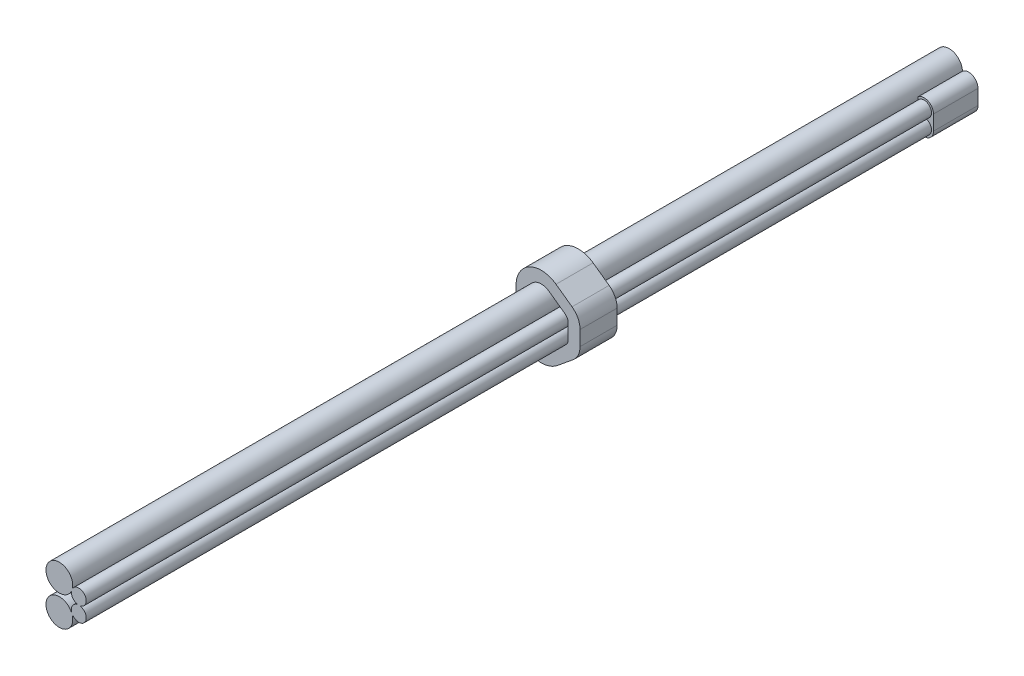
SolidWorks part; units mm, degrees
material "PVC 0.007 Plasticized"
ref_plane "Front Plane" through (0, 0, 0) normal (0, 0, 1) x (1, 0, 0)
ref_plane "Top Plane" through (0, 0, 0) normal (0, 1, 0) x (1, 0, 0)
ref_plane "Right Plane" through (0, 0, 0) normal (1, 0, 0) x (0, 0, -1)
ref_plane "Plane1" through (0, 0, 27.5) normal (0, 0, 1) x (1, 0, 0)
sketch "Sketch1" plane through (0, 0, 27.5) normal (0, 0, 1) x (1, 0, 0)
  line L0 (0.6794, -0.5903) -> (0.6794, -1.4197)
  line L1 (-0.9, -2.01) -> (-0.9, 0)
  line L2 (1.6306, -1.8389) -> (0.5699, -2.7066)
  line L3 (0.8727, -1.7901) -> (0.924, -1.7648)
  line L4 (0.5253, 0.7308) -> (1.6058, -0.0459)
  line L5 (0.8783, -0.2065) -> (0.8762, -0.2056)
  line L6 (1.814, -0.4519) -> (1.814, -1.4519)
  line L7 (1.4095, -0.9611) -> (1.4125, -0.9421)
  line L8 (-1.7, 0) -> (-1.7, -2.01)
  line L9 (1.0764, -3.3258) -> (2.614, -2.068)
  line L10 (2.614, -2.068) -> (2.614, 0.2146)
  line L11 (2.614, 0.2146) -> (0.9922, 1.3804)
  arc A0 (-0.9, 0) -> (0.6794, -0.5903) centre (0, 0) ccw
  arc A1 (0.6794, -1.4197) -> (-0.9, -2.01) centre (0, -2.01) ccw
  arc A2 (0.5699, -2.7066) -> (0.8727, -1.7901) centre (0, -2.01) ccw
  arc A3 (0.924, -1.7648) -> (1.6306, -1.8389) centre (1.314, -1.4519) ccw
  arc A4 (1.6058, -0.0459) -> (0.8783, -0.2065) centre (1.314, -0.4519) ccw
  arc A5 (0.8762, -0.2056) -> (0.5253, 0.7308) centre (0, 0) ccw
  arc A6 (1.814, -1.4519) -> (1.4095, -0.9611) centre (1.314, -1.4519) ccw
  arc A7 (1.4125, -0.9421) -> (1.814, -0.4519) centre (1.314, -0.4519) ccw
  arc A8 (-1.7, -2.01) -> (1.0764, -3.3258) centre (0, -2.01) ccw
  arc A9 (0.9922, 1.3804) -> (-1.7, 0) centre (0, 0) ccw
extrude "Boss-Extrude1" add sketch "Sketch1" against normal blind 2.5
sketch "Sketch2" plane through (0, 0, 25) normal (0, 0, -1) x (-1, 0, 0)
  line L0 (-0.8727, -1.7901) -> (-0.924, -1.7648)
  line L1 (-1.4095, -0.9611) -> (-1.4125, -0.9421)
  line L2 (-0.8783, -0.2065) -> (-0.8762, -0.2056)
  line L3 (-0.6794, -0.5903) -> (-0.6794, -1.4197)
  arc A0 (-0.6794, -1.4197) -> (-0.8727, -1.7901) centre (0, -2.01) cw
  arc A1 (-0.924, -1.7648) -> (-1.4095, -0.9611) centre (-1.314, -1.4519) cw
  arc A2 (-1.4125, -0.9421) -> (-0.8783, -0.2065) centre (-1.314, -0.4519) cw
  arc A3 (-0.8762, -0.2056) -> (-0.6794, -0.5903) centre (0, 0) cw
extrude "Boss-Extrude2" add sketch "Sketch2" along normal blind 22
sketch "Sketch3" plane through (0, 0, 3) normal (0, 0, -1) x (-1, 0, 0)
  line L0 (-0.6794, -0.5903) -> (-0.6794, -1.4197)
  line L1 (-1.9486, -1.4519) -> (-1.9486, -0.4519)
  arc A0 (-1.9486, -0.4519) -> (-0.8995, 0.0287) centre (-1.314, -0.4519) cw
  arc A1 (-0.8995, 0.0287) -> (-0.6794, -0.5903) centre (0, 0) cw
  arc A2 (-0.6794, -1.4197) -> (-0.8964, -1.9298) centre (0, -2.01) cw
  arc A3 (-0.8964, -1.9298) -> (-1.9486, -1.4519) centre (-1.314, -1.4519) cw
extrude "Boss-Extrude3" add sketch "Sketch3" along normal blind 3
sketch "Sketch4" plane through (0, 0, 27.5) normal (0, 0, 1) x (1, 0, 0)
  line L0 (0.6794, -0.5903) -> (0.6794, -1.4197)
  line L1 (0.8045, -1.6065) -> (0.8339, -1.5918)
  line L2 (1.1979, -0.9656) -> (1.1979, -0.9382)
  line L3 (0.8192, -0.3798) -> (0.8166, -0.3784)
  arc A0 (0.8166, -0.3784) -> (0.6794, -0.5903) centre (0, 0) cw
  arc A1 (0.6794, -1.4197) -> (0.8045, -1.6065) centre (0, -2.01) cw
  arc A2 (0.8339, -1.5918) -> (1.1979, -0.9656) centre (1.314, -1.4519) cw
  arc A3 (1.1979, -0.9382) -> (0.8192, -0.3798) centre (1.314, -0.4519) cw
extrude "Cut-Extrude1" cut sketch "Sketch4" against normal blind 24.5
sketch "Sketch5" plane through (0, 0, 27.5) normal (0, 0, 1) x (1, 0, 0)
  line L0 (0.924, -1.7648) -> (0.8727, -1.7901)
  line L1 (0.8045, -1.6065) -> (0.8339, -1.5918)
  line L2 (1.1979, -0.9656) -> (1.1979, -0.9382)
  line L3 (0.8192, -0.3798) -> (0.8166, -0.3784)
  line L4 (0.8762, -0.2056) -> (0.8783, -0.2065)
  line L5 (1.4125, -0.9421) -> (1.4095, -0.9611)
  arc A0 (0.8727, -1.7901) -> (0.8045, -1.6065) centre (0, -2.01) cw
  arc A1 (0.8339, -1.5918) -> (1.1979, -0.9656) centre (1.314, -1.4519) cw
  arc A2 (1.1979, -0.9382) -> (0.8192, -0.3798) centre (1.314, -0.4519) cw
  arc A3 (0.8166, -0.3784) -> (0.8762, -0.2056) centre (0, 0) cw
  arc A4 (0.8783, -0.2065) -> (1.4125, -0.9421) centre (1.314, -0.4519) cw
  arc A5 (1.4095, -0.9611) -> (0.924, -1.7648) centre (1.314, -1.4519) cw
extrude "Boss-Extrude4" add sketch "Sketch5" along normal blind 32.5
fillet "Fillet1" radius 1.3 2 edges at (2.614, -2.068, 26.25) (2.614, 0.2146, 26.25)
